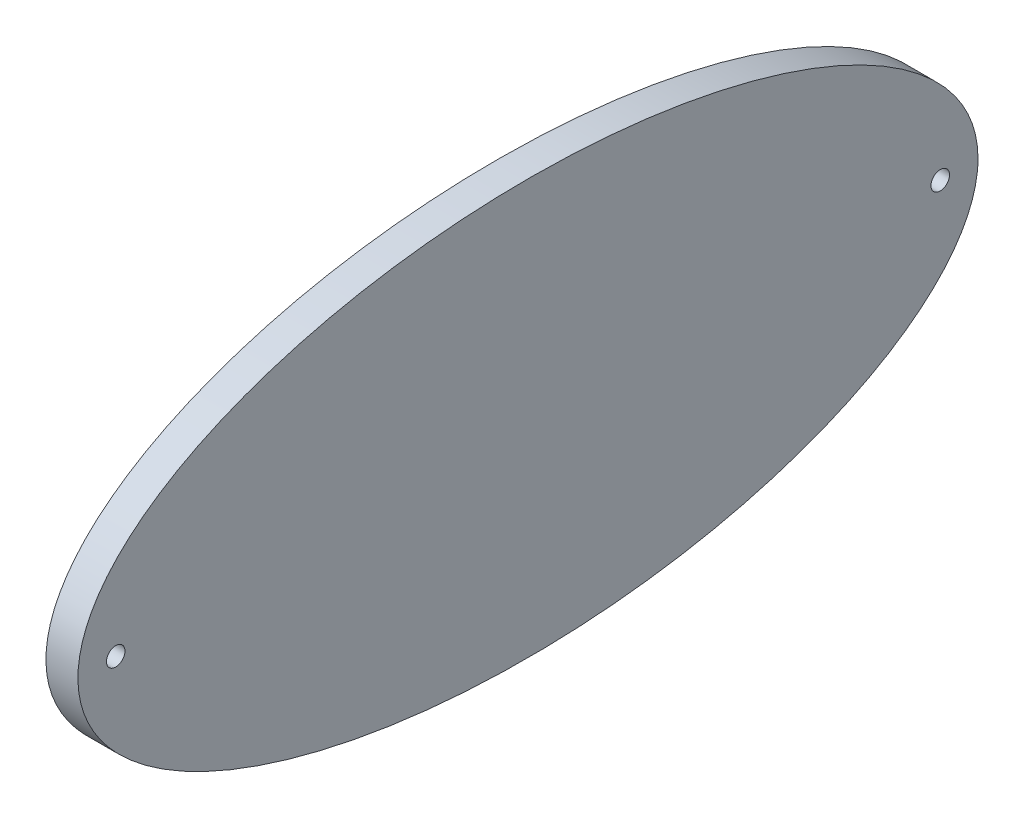
SolidWorks part; units mm, degrees
ref_plane "Front Plane" through (0, 0, 0) normal (0, 0, 1) x (1, 0, 0)
ref_plane "Top Plane" through (0, 0, 0) normal (0, 1, 0) x (1, 0, 0)
ref_plane "Right Plane" through (0, 0, 0) normal (1, 0, 0) x (0, 0, -1)
sketch "Sketch1" plane through (0, 0, 0) normal (1, 0, 0) x (0, 0, -1)
  circle A0 centre (-65.5, 0) radius 1.4732
  circle A1 centre (65.5, 0) radius 1.4732
  ellipse E0 centre (0, 0) end of major axis (71.5, 0) minor radius 32.95
  dimension "D3" = 2.9464
  dimension "D4" = 2.9464
  dimension "D1" = 65.9
  dimension "D2" = 143
  dimension "D5" = 6
  dimension "D6" = 6
extrude "Boss-Extrude1" add sketch "Sketch1" along normal blind 5.08
